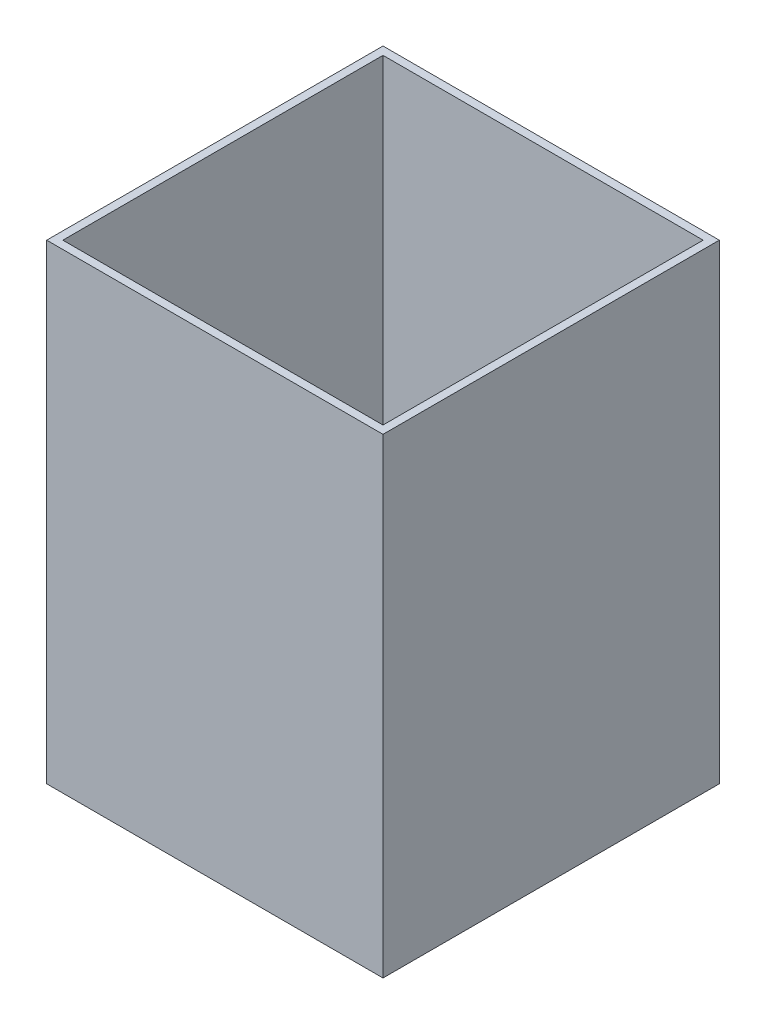
SolidWorks part; units mm, degrees
ref_plane "Front" through (0, 0, 0) normal (0, 0, 1) x (1, 0, 0)
ref_plane "Top" through (0, 0, 0) normal (0, 1, 0) x (1, 0, 0)
ref_plane "Right" through (0, 0, 0) normal (1, 0, 0) x (0, 0, -1)
sketch "Sketch1" plane through (0, 0, 0) normal (0, 1, 0) x (1, 0, 0)
  line L1 (-125, -125) -> (125, -125)
  line L2 (-125, -125) -> (-125, 125)
  line L3 (-125, 125) -> (125, 125)
  line L4 (125, -125) -> (125, 125)
  line L5 (-125, -125) -> (125, 125) construction
  line L6 (-125, 125) -> (125, -125) construction
  point P0 (0, 0)
  dimension "D1" = 250
  dimension "D2" = 250
extrude "Boss-Extrude1" add sketch "Sketch1" along normal blind 350
sketch "Sketch2" plane through (0, 350, 0) normal (0, 1, 0) x (1, 0, 0)
  line L0 (125, -125) -> (125, 125) construction
  line L1 (-119, 119) -> (119, 119)
  line L2 (-119, 119) -> (-119, -119)
  line L3 (-119, -119) -> (119, -119)
  line L4 (119, 119) -> (119, -119)
  line L5 (-119, 119) -> (119, -119) construction
  line L6 (-119, -119) -> (119, 119) construction
  line L7 (125, 125) -> (-125, 125) construction
  point P0 (0, 0)
  dimension "D1" = 6
  dimension "D2" = 6
extrude "Cut-Extrude1" cut sketch "Sketch2" against normal through all
